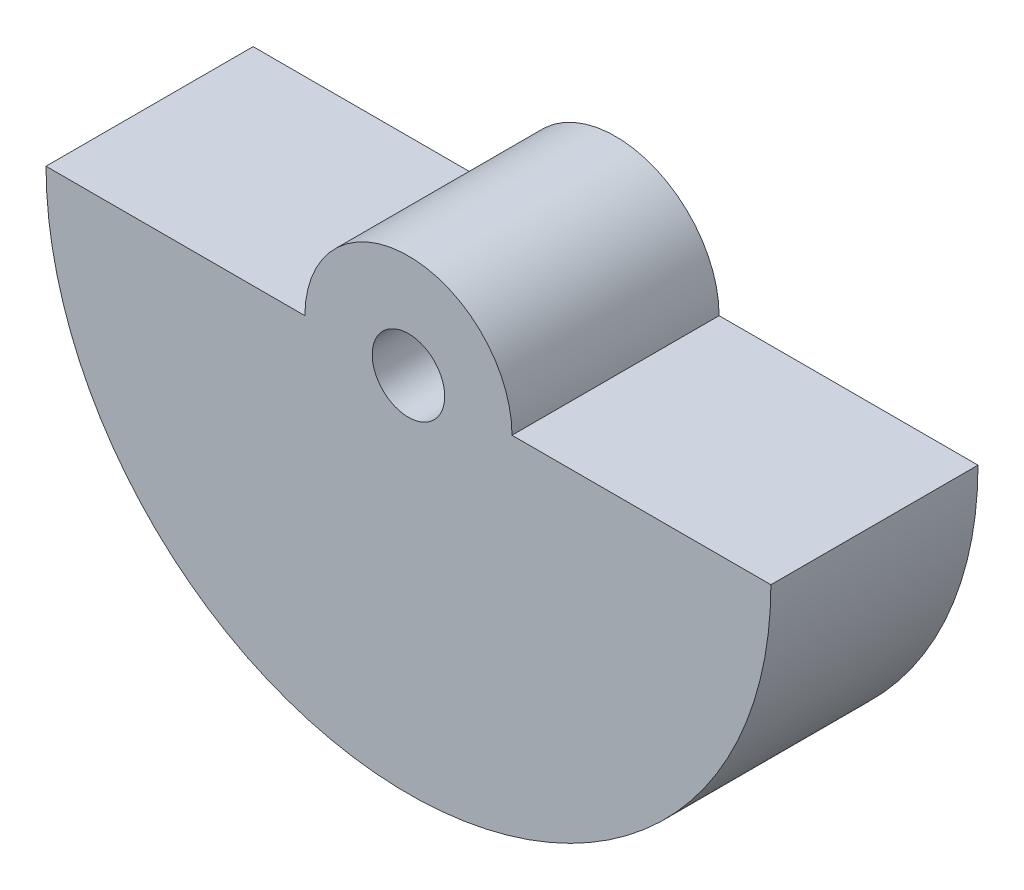
SolidWorks part; units mm, degrees
ref_plane "Front Plane" through (0, 0, 0) normal (0, 0, 1) x (1, 0, 0)
ref_plane "Top Plane" through (0, 0, 0) normal (0, 1, 0) x (1, 0, 0)
ref_plane "Right Plane" through (0, 0, 0) normal (1, 0, 0) x (0, 0, -1)
sketch "Sketch1" plane through (0, 0, 0) normal (0, 0, 1) x (1, 0, 0)
  line L0 (-35, 0) -> (-10, 0)
  line L2 (10, 0) -> (35, 0)
  arc A0 (-35, 0) -> (35, 0) centre (0, 0) ccw
  arc A1 (10, 0) -> (-10, 0) centre (0, 0) ccw
  circle A2 centre (0, 0) radius 3.5
  dimension "D1" = 70
  dimension "D2" = 20
  dimension "D3" = 7
extrude "Boss-Extrude1" add sketch "Sketch1" along normal blind 20
